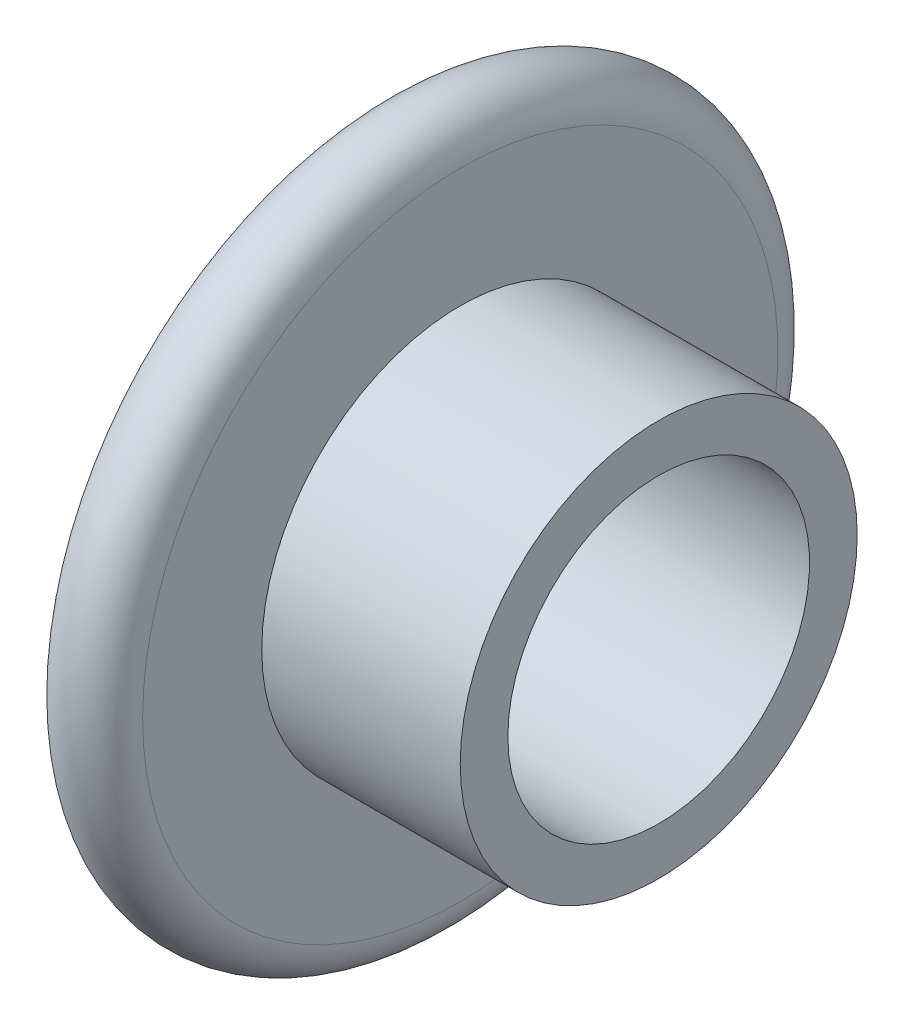
SolidWorks part; units mm, degrees
ref_plane "Front Plane" through (0, 0, 0) normal (0, 0, 1) x (1, 0, 0)
ref_plane "Top Plane" through (0, 0, 0) normal (0, 1, 0) x (1, 0, 0)
ref_plane "Right Plane" through (0, 0, 0) normal (1, 0, 0) x (0, 0, -1)
sketch "Sketch1" plane through (0, 0, 0) normal (0, 0, 1) x (1, 0, 0)
  line L0 (0, 0) -> (45, 0) construction
  line L1 (0, 19) -> (45, 19)
  line L2 (45, 19) -> (45, 25)
  line L3 (45, 25) -> (20, 25)
  line L4 (20, 25) -> (20, 40)
  line L5 (10, 40) -> (10, 25)
  line L6 (10, 25) -> (0, 25)
  line L7 (0, 25) -> (0, 19)
  arc A0 (20, 40) -> (10, 40) centre (15, 40) ccw
  point P10 (45, 0)
  point P13 (15, 45)
  point P14 (21.8742, 40)
  dimension "D1" = 5
  dimension "D2" = 10
  dimension "D3" = 25
  dimension "D4" = 25
  dimension "D5" = 45
  dimension "D6" = 19
revolve "Revolve1" add sketch "Sketch1" angle 360 about L0
